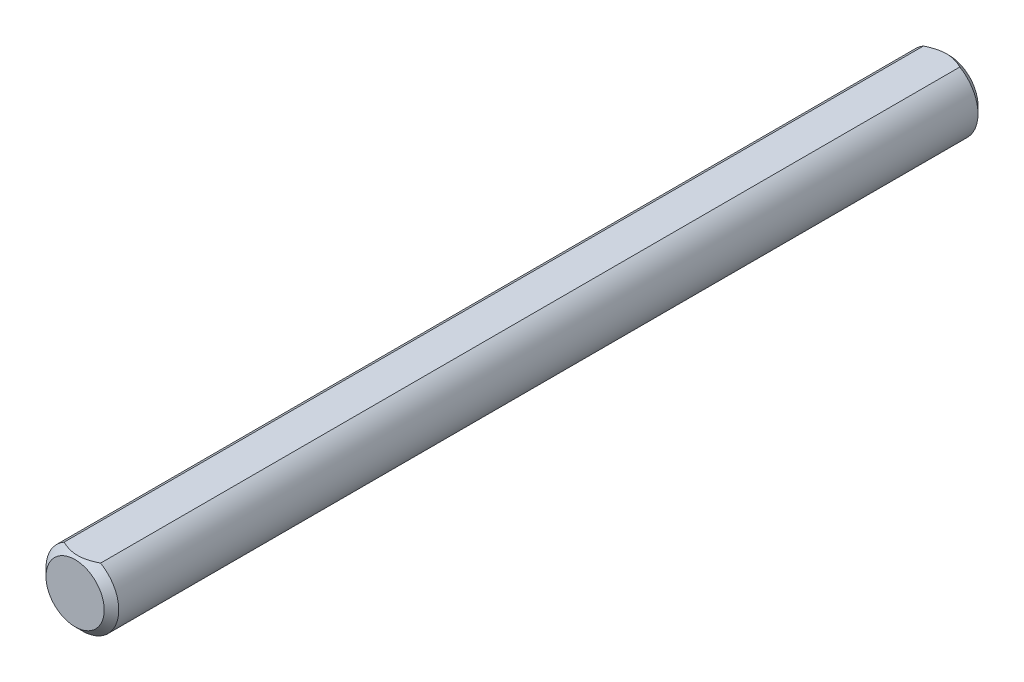
SolidWorks part; units mm, degrees
ref_plane "Front" through (0, 0, 0) normal (0, 0, 1) x (1, 0, 0)
ref_plane "Top" through (0, 0, 0) normal (0, 1, 0) x (1, 0, 0)
ref_plane "Right" through (0, 0, 0) normal (1, 0, 0) x (0, 0, -1)
sketch "Sketch1" plane through (0, 0, 0) normal (0, 0, 1) x (1, 0, 0)
  circle A0 centre (0, 0) radius 6.35
  dimension "D1" = 12.7
extrude "Extrude1" add sketch "Sketch1" along normal mid plane 152.4
chamfer "Chamfer1" distance 1.27 angle 45 2 edges at (6.35, 0, -76.2) (6.35, 0, 76.2)
sketch "Sketch13" plane through (0, 0, 0) normal (0, 0, 1) x (1, 0, 0)
  line L3 (-3.175, 5.4993) -> (3.175, 5.4993)
  circle A0 centre (0, 0) radius 6.35 construction
  arc A1 (3.175, 5.4993) -> (-3.175, 5.4993) centre (0, 0) ccw
  dimension "D1" = 6.35
extrude "Extrude7" cut sketch "Sketch13" against normal through all and the other way through all
equation "\"D1@Chamfer1\" = \"D1@Sketch1\" * .1"
equation "\"D1@Sketch13\" = \"D1@Sketch1\" * .5"
